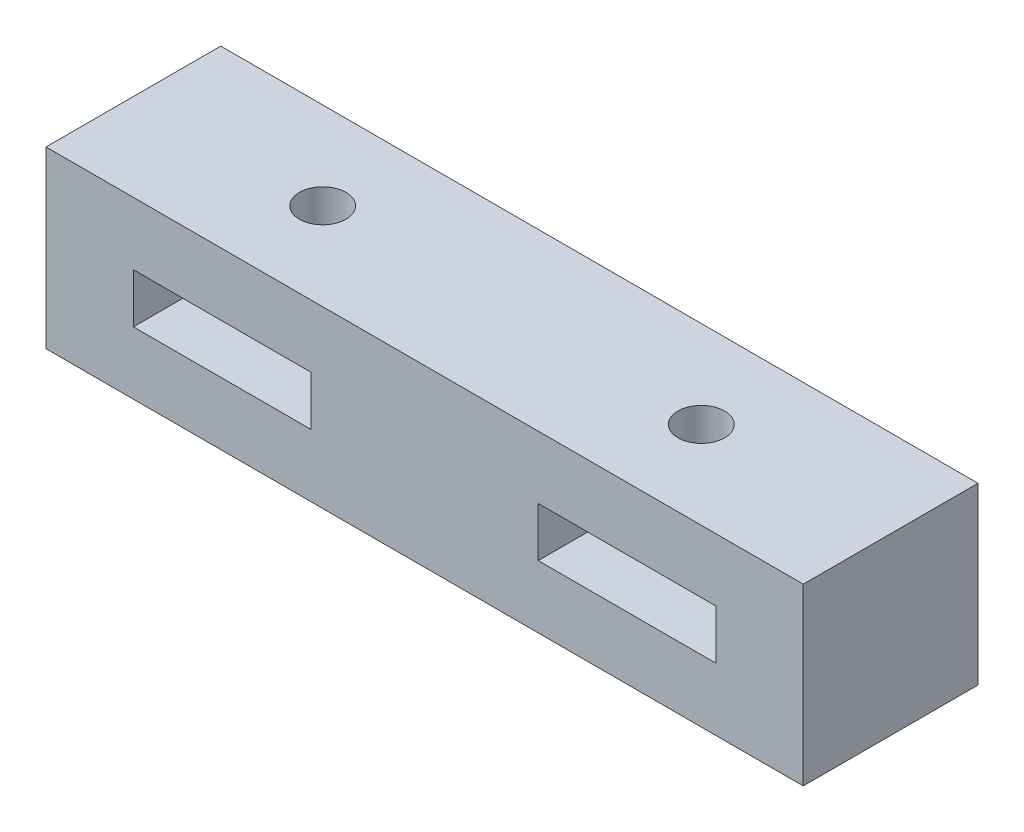
SolidWorks part; units mm, degrees
ref_plane "Alzado" through (0, 0, 0) normal (0, 0, 1) x (1, 0, 0)
ref_plane "Planta" through (0, 0, 0) normal (0, 1, 0) x (1, 0, 0)
ref_plane "Vista lateral" through (0, 0, 0) normal (1, 0, 0) x (0, 0, -1)
sketch "Croquis1" plane through (0, 0, 0) normal (0, 0, 1) x (1, 0, 0)
  line L0 (0, 0) -> (-26, 0) construction
  line L1 (-26, -6) -> (26, -6)
  line L2 (-26, -6) -> (-26, 6)
  line L3 (-26, 6) -> (26, 6)
  line L4 (26, -6) -> (26, 6)
  line L5 (-26, -6) -> (26, 6) construction
  line L6 (-26, 6) -> (26, -6) construction
  line L7 (0, 6) -> (0, -6) construction
  line L8 (20, 1.7) -> (7.8, 1.7)
  line L9 (-20, -1.7) -> (-7.8, -1.7)
  line L10 (-20, -1.7) -> (-20, 1.7)
  line L11 (-20, 1.7) -> (-7.8, 1.7)
  line L12 (-7.8, -1.7) -> (-7.8, 1.7)
  line L13 (-20, -1.7) -> (-7.8, 1.7) construction
  line L14 (-20, 1.7) -> (-7.8, -1.7) construction
  line L15 (7.8, -1.7) -> (7.8, 1.7)
  line L16 (20, -1.7) -> (7.8, -1.7)
  line L17 (20, -1.7) -> (20, 1.7)
  point P0 (0, 0)
  point P10 (-13.9, 0)
  dimension "D1" = 12
  dimension "D2" = 52
  dimension "D3" = 20
  dimension "D4" = 12.2
  dimension "D5" = 3.4
extrude "Saliente-Extruir1" add sketch "Croquis1" along normal mid plane 12
sketch "Croquis2" plane through (0, 0, -6) normal (0, 0, -1) x (-1, 0, 0)
  circle A0 centre (0, 0) radius 4.15
  dimension "D1" = 8.3
extrude "Cortar-Extruir1" cut sketch "Croquis2" against normal blind 9
sketch "Croquis3" plane through (0, 6, 0) normal (0, 1, 0) x (1, 0, 0)
  line L0 (-13, 6) -> (-13, -6) construction
  line L1 (26, 6) -> (-26, 6) construction
  line L2 (26, -6) -> (-26, -6) construction
  line L3 (0, 6) -> (0, -6) construction
  circle A0 centre (-13, 0) radius 1.6
  circle A1 centre (13, 0) radius 1.6
  dimension "D2" = 3.2
  dimension "D1" = 13
extrude "Cortar-Extruir2" cut sketch "Croquis3" against normal blind 30
